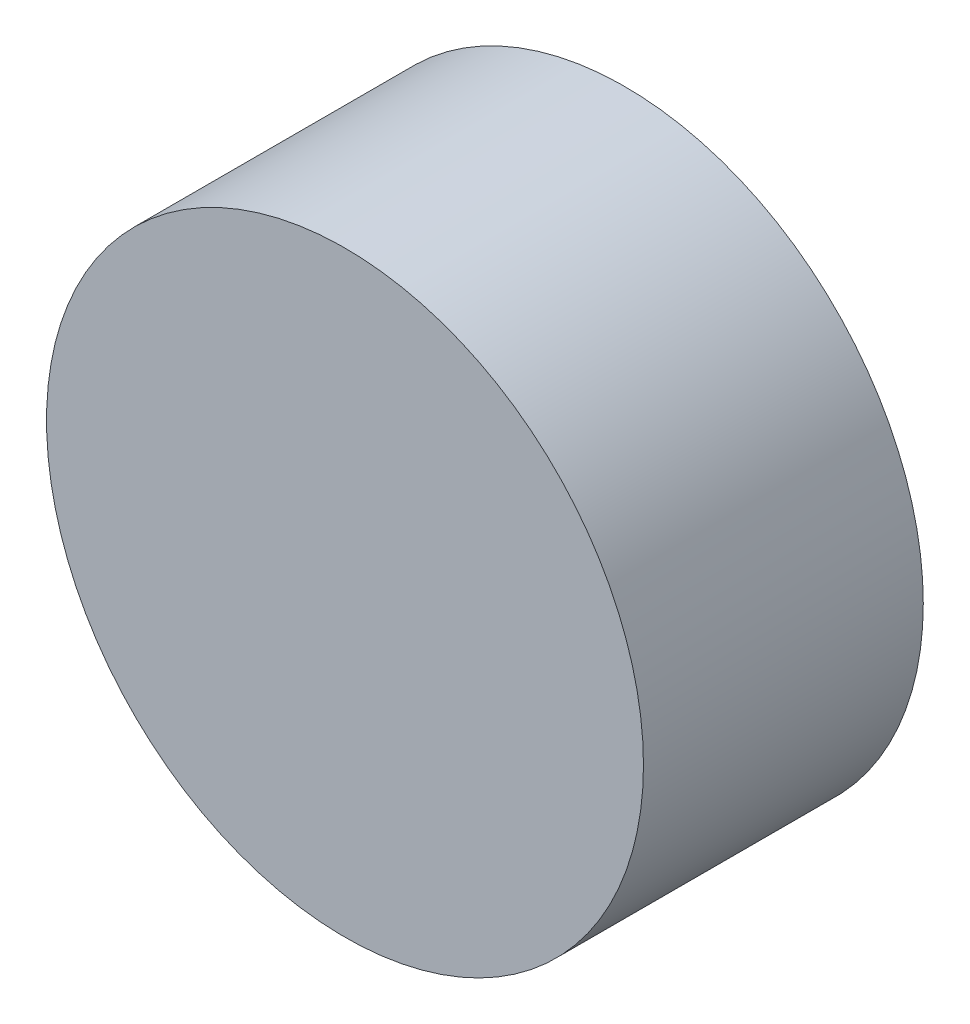
SolidWorks part; units mm, degrees
ref_plane "Front Plane" through (0, 0, 0) normal (0, 0, 1) x (1, 0, 0)
ref_plane "Top Plane" through (0, 0, 0) normal (0, 1, 0) x (1, 0, 0)
ref_plane "Right Plane" through (0, 0, 0) normal (1, 0, 0) x (0, 0, -1)
sketch "Sketch2" plane through (0, 0, 0) normal (0, 0, 1) x (1, 0, 0)
  circle A0 centre (0, 0) radius 32
  dimension "D1" = 32
extrude "Boss-Extrude1" add sketch "Sketch2" along normal blind 30
